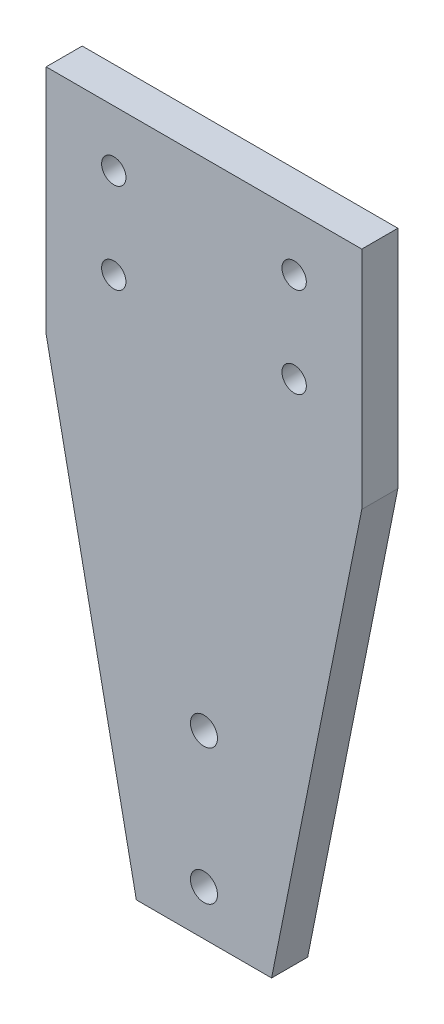
SolidWorks part; units mm, degrees
ref_plane "Front Plane" through (0, 0, 0) normal (0, 0, 1) x (1, 0, 0)
ref_plane "Top Plane" through (0, 0, 0) normal (0, 1, 0) x (1, 0, 0)
ref_plane "Right Plane" through (0, 0, 0) normal (1, 0, 0) x (0, 0, -1)
sketch "Sketch1" plane through (0, 0, 0) normal (0, 0, 1) x (1, 0, 0)
  line L0 (0, 0) -> (38.1, 0)
  line L1 (38.1, 0) -> (63.5, 127)
  line L2 (63.5, 127) -> (63.5, 190.5)
  line L3 (63.5, 190.5) -> (-25.4, 190.5)
  line L4 (-25.4, 190.5) -> (-25.4, 125.2916)
  line L5 (-25.4, 125.2916) -> (0, 0)
  line L6 (-12.7, 190.5) -> (12.7, 190.5)
  circle A0 centre (19.05, 12.7) radius 3.81
  circle A1 centre (19.05, 50.8) radius 3.81
  circle A2 centre (-6.35, 174.6877) radius 3.429
  circle A3 centre (-6.35, 149.2877) radius 3.429
  circle A4 centre (44.45, 149.2877) radius 3.429
  circle A5 centre (44.45, 174.6877) radius 3.429
  point P4 (19.05, 0)
  point P8 (19.05, 190.5)
  dimension "D5" = 7.62
  dimension "D9" = 7.62
  dimension "D11" = 6.858
  dimension "D13" = 19.05
  dimension "D1" = 63.5
  dimension "D2" = 88.9
  dimension "D3" = 38.1
  dimension "D4" = 190.5
  dimension "D6" = 12.7
  dimension "D7" = 19.05
  dimension "D8" = 38.1
  dimension "D10" = 19.05
  dimension "D12" = 25.4
extrude "Boss-Extrude1" add sketch "Sketch1" along normal blind 10.16 contours L5 L0 L1 L2 L3 L4 | A2 | A3 | A5 | A4 | A1 | A0
